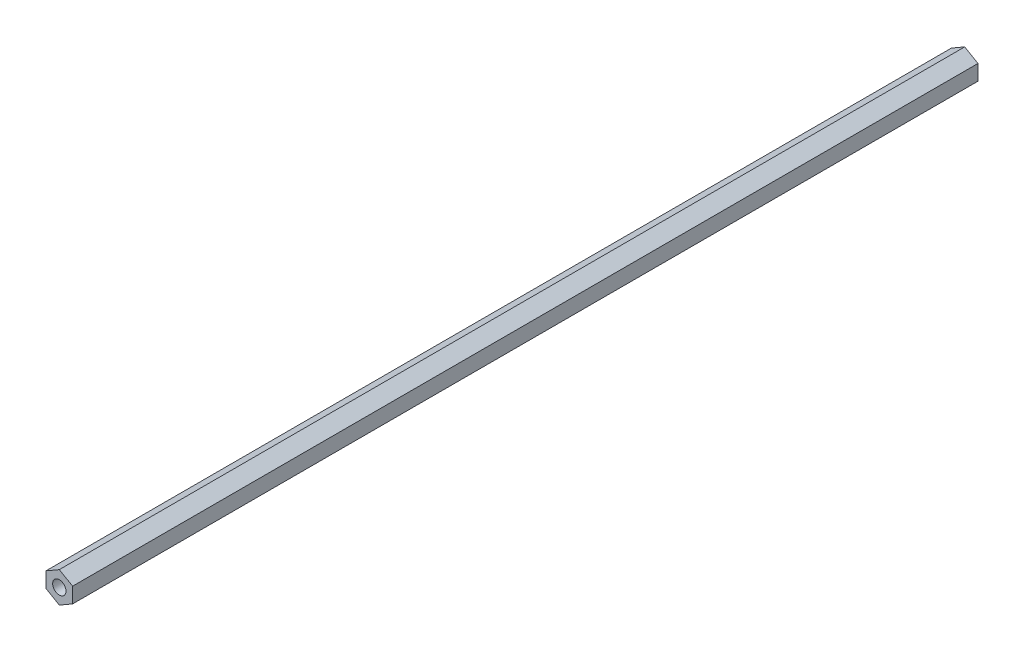
SolidWorks part; units mm, degrees
material "AISI 1020 Steel, Cold Rolled"
ref_plane "Front Plane" through (0, 0, 0) normal (0, 0, 1) x (1, 0, 0)
ref_plane "Top Plane" through (0, 0, 0) normal (0, 1, 0) x (1, 0, 0)
ref_plane "Right Plane" through (0, 0, 0) normal (1, 0, 0) x (0, 0, -1)
sketch "Sketch1" plane through (0, 0, 0) normal (0, 0, 1) x (1, 0, 0)
  line L1 (0, 7.3323) -> (-6.35, 3.6662) construction
  line L2 (-6.35, 3.6662) -> (-6.35, -3.6662) construction
  line L3 (-6.35, -3.6662) -> (0, -7.3323) construction
  line L4 (0, -7.3323) -> (6.35, -3.6662) construction
  line L5 (6.35, -3.6662) -> (6.35, 3.6662) construction
  line L6 (6.35, 3.6662) -> (0, 7.3323) construction
  circle A2 centre (0, 0) radius 6.35 construction
  dimension "Width" = 12.7
sketch "Sketch2" plane through (0, 0, 0) normal (1, 0, 0) x (0, 0, -1)
  line L0 (-216.027, 7.3323) -> (216.027, 7.3323) construction
  point P2 (0, 7.3323)
  point P3 (184.277, 7.3323)
  point P4 (-184.277, 7.3323)
  dimension "Length" = 432.054
  dimension "D2" = 31.75
  dimension "D1" = 31.75
sketch "Sketch3" plane through (0, 0, 0) normal (0, 0, 1) x (1, 0, 0)
  line L0 (-6.35, -3.6662) -> (0, -7.3323) construction
  line L1 (0, -7.3323) -> (6.35, -3.6662) construction
  line L2 (6.35, -3.6662) -> (6.35, 3.6662) construction
  line L3 (6.35, 3.6662) -> (0, 7.3323) construction
  line L4 (0, 7.3323) -> (-6.35, 3.6662) construction
  line L5 (-6.35, 3.6662) -> (-6.35, -3.6662) construction
  line L6 (-6.35, -3.6662) -> (0, -7.3323)
  line L7 (0, -7.3323) -> (6.35, -3.6662)
  line L8 (6.35, -3.6662) -> (6.35, 3.6662)
  line L9 (6.35, 3.6662) -> (0, 7.3323)
  line L10 (0, 7.3323) -> (-6.35, 3.6662)
  line L11 (-6.35, 3.6662) -> (-6.35, -3.6662)
extrude "Boss-Extrude2" add sketch "Sketch3" along normal up to vertex (216.027 mm away) and the other way up to vertex (216.027 mm away) up to point (0, 7.3323, 216.027) other way up to point (0, 7.3323, -216.027)
sketch "Sketch4" plane through (0, 0, 216.027) normal (0, 0, 1) x (1, 0, 0)
  point P0 (0, 0)
hole_wizard "1/4 (0.25) Diameter Hole1" positions "Sketch5" profile "Sketch6" hole size "1/4" standard "ANSI Inch"
sketch "Sketch5" plane through (0, 0, 216.027) normal (0, 0, 1) x (1, 0, 0)
  point P0 (0, 0)
sketch "Sketch6" plane through (0, 0, 216.027) normal (1, 0, 0) x (0, -1, 0)
  line L0 (0, 0) -> (0, 27.3077)
  line L1 (0, 27.3077) -> (3.175, 25.4)
  line L2 (3.175, 25.4) -> (3.175, 0)
  line L5 (3.175, 0) -> (0, 0)
  line L10 (0, 27.3077) -> (-3.175, 25.4) construction
  line L11 (0, -6.35) -> (0, 107.95) construction
  dimension "Hole Dia." = 6.35
  dimension "Hole Depth" = 25.4
  dimension "Drill Angle" = 118
hole_wizard "1/4 (0.25) Diameter Hole2" positions "Sketch7" profile "Sketch8" hole size "1/4" standard "ANSI Inch"
sketch "Sketch7" plane through (0, 0, -216.027) normal (0, 0, -1) x (-1, 0, 0)
  point P0 (0, 0)
sketch "Sketch8" plane through (0, 0, -216.027) normal (1, 0, 0) x (0, 1, 0)
  line L0 (0, 0) -> (0, 27.3077)
  line L1 (0, 27.3077) -> (3.175, 25.4)
  line L2 (3.175, 25.4) -> (3.175, 0)
  line L5 (3.175, 0) -> (0, 0)
  line L10 (0, 27.3077) -> (-3.175, 25.4) construction
  line L11 (0, -6.35) -> (0, 107.95) construction
  dimension "Hole Dia." = 6.35
  dimension "Hole Depth" = 25.4
  dimension "Drill Angle" = 118
equation "\"D2@Sketch2\" = \"D1@Sketch2\""
equation "\"D1@Sketch2\" = \"Width@Sketch1\" * 2.5"
